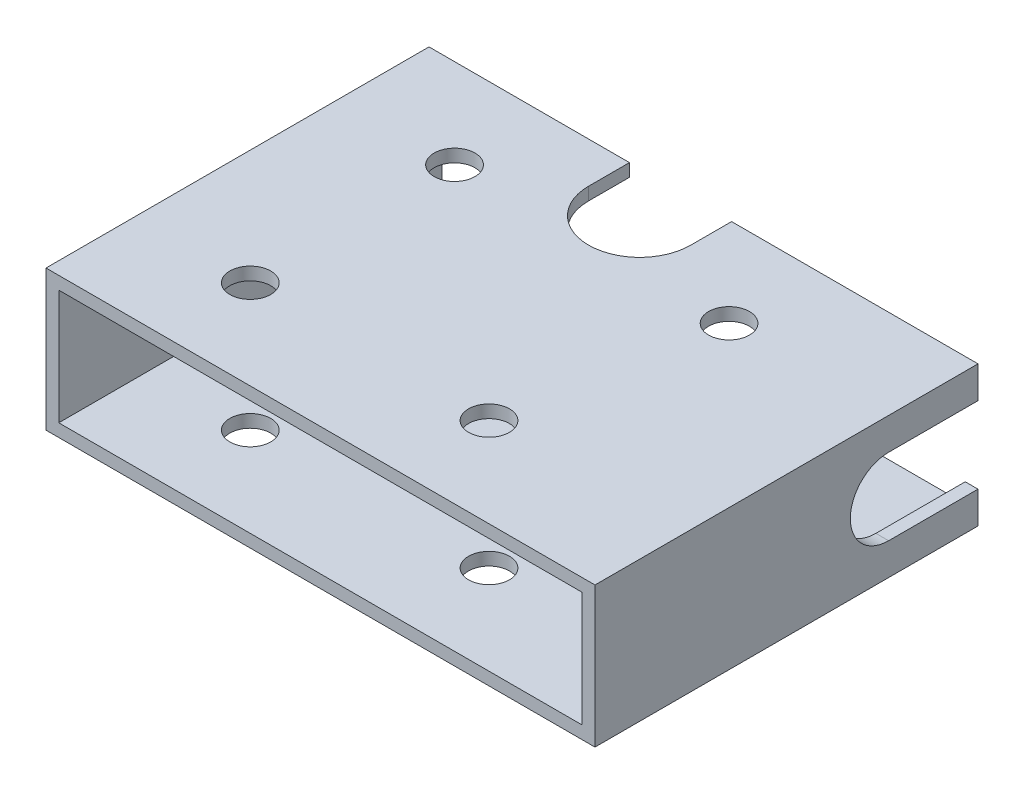
SolidWorks part; units mm, degrees
ref_plane "前视基准面" through (0, 0, 0) normal (0, 0, 1) x (1, 0, 0)
ref_plane "上视基准面" through (0, 0, 0) normal (0, 1, 0) x (1, 0, 0)
ref_plane "右视基准面" through (0, 0, 0) normal (1, 0, 0) x (0, 0, -1)
sketch "草图2" plane through (0, 0, 0) normal (0, 0, 1) x (1, 0, 0)
  line L0 (0, 0) -> (-43, 0)
  line L1 (-43, 0) -> (-43, 11)
  line L2 (-43, 11) -> (0, 11)
  line L3 (0, 11) -> (0, 10)
  line L4 (-1, 10) -> (-42, 10)
  line L5 (-42, 10) -> (-42, 1)
  line L6 (-42, 1) -> (-1, 1)
  line L7 (0, 1) -> (0, 0)
  line L8 (0, 1) -> (0, 10)
  line L9 (-1, 1) -> (-1, 10)
  dimension "D1" = 1
  dimension "D2" = 1
  dimension "D3" = 1
  dimension "D4" = 43
  dimension "D5" = 9
  dimension "D6" = 1
extrude "凸台-拉伸1" add sketch "草图2" along normal blind 30
sketch "草图3" plane through (0, 11, 0) normal (0, 1, 0) x (1, 0, 0)
  line L0 (-43, -30) -> (-43, 0) construction
  line L1 (-43, -15) -> (9.3662, -15) construction
  circle A0 centre (-34, -7) radius 1.6
  circle A1 centre (-34, -23) radius 1.6
  circle A2 centre (-15.3, -23) radius 1.6
  circle A3 centre (-12.5, -7) radius 1.6
  dimension "D1" = 3.2
  dimension "D2" = 9
  dimension "D4" = 16
  dimension "D5" = 3.2
  dimension "D6" = 21.5
  dimension "D7" = 27.7
extrude "切除-拉伸1" cut sketch "草图3" against normal through all
sketch "草图4" plane through (0, 11, 0) normal (0, 1, 0) x (1, 0, 0)
  line L0 (-23.3, -30.8629) -> (-23.3, -9.566) construction
  line L1 (-43, -30) -> (-43, 0) construction
  line L2 (-19.3, -30) -> (-27.3, -30) construction
  line L3 (0, -30) -> (-43, -30) construction
  line L4 (-27.3, -30) -> (-27.3, -26.8) construction
  line L5 (-19.3, -30) -> (-19.3, -26.8) construction
  line L6 (-43, -15) -> (6.9453, -15) construction
  line L7 (-19.3, 0) -> (-19.3, -3.2)
  line L8 (-27.3, 0) -> (-27.3, -3.2)
  line L9 (-19.3, 0) -> (-27.3, 0)
  arc A0 (-19.3, -26.8) -> (-27.3, -26.8) centre (-23.3, -26.8) ccw construction
  arc A1 (-19.3, -3.2) -> (-27.3, -3.2) centre (-23.3, -3.2) cw
  point P14 (-23.3, -30)
  dimension "D2" = 4
  dimension "D1" = 19.7
  dimension "D3" = 4
  dimension "D4" = 3.2
extrude "切除-拉伸2" cut sketch "草图4" against normal blind 3
sketch "草图6" plane through (0, 1, 0) normal (0, 1, 0) x (1, 0, 0)
  line L0 (-28.3, -3.2) -> (-28.3, 0)
  line L1 (-27.3, 0) -> (-43, 0) construction
  line L2 (-28.3, 0) -> (-18.3, 0)
  line L3 (0, 0) -> (-19.3, 0) construction
  line L4 (-18.3, 0) -> (-18.3, -3.2)
  arc A0 (-18.3, -3.2) -> (-28.3, -3.2) centre (-23.3, -3.2) cw
  dimension "D1" = 5
extrude "切除-拉伸3" cut sketch "草图6" against normal blind 3
sketch "草图7" plane through (0, 0, 0) normal (1, 0, 0) x (0, 0, -1)
  line L0 (-30, 5.5) -> (2.3046, 5.5) construction
  line L1 (-30, 0) -> (-30, 11) construction
  line L2 (-7, 8.5) -> (0, 8.5)
  line L3 (0, 0) -> (0, 11) construction
  line L4 (-7, 2.5) -> (0, 2.5)
  line L5 (0, 2.5) -> (0, 8.5)
  arc A0 (-7, 8.5) -> (-7, 2.5) centre (-7, 5.5) ccw
  dimension "D1" = 3
  dimension "D2" = 7
extrude "切除-拉伸4" cut sketch "草图7" against normal blind 3
